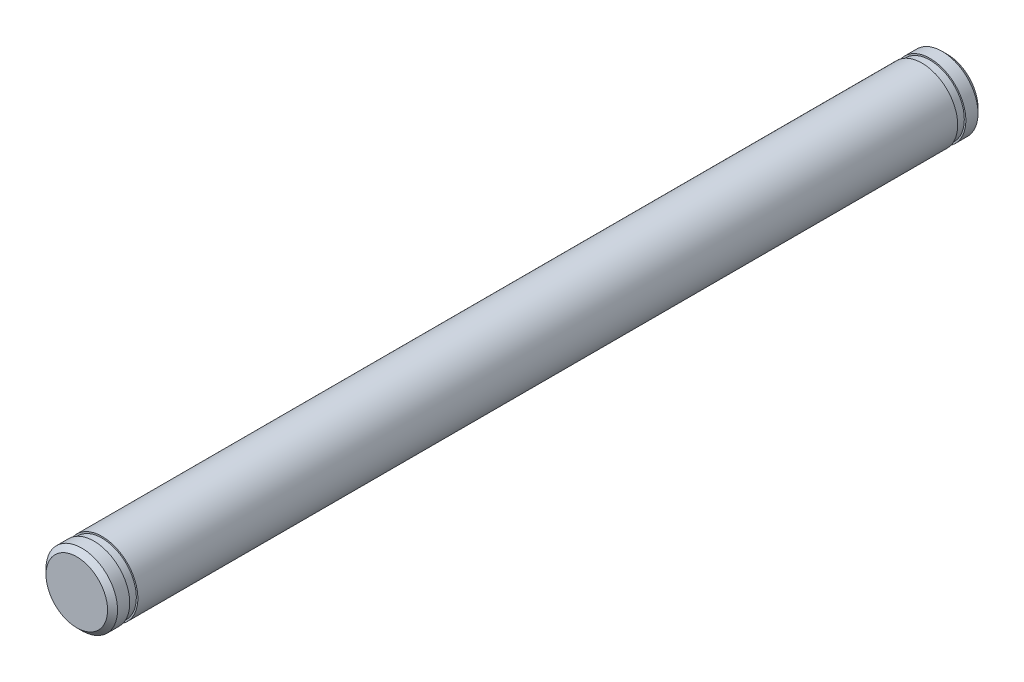
SolidWorks part; units mm, degrees
ref_plane "Front Plane" through (0, 0, 0) normal (0, 0, 1) x (1, 0, 0)
ref_plane "Top Plane" through (0, 0, 0) normal (0, 1, 0) x (1, 0, 0)
ref_plane "Right Plane" through (0, 0, 0) normal (1, 0, 0) x (0, 0, -1)
sketch "Sketch1" plane through (0, 0, 0) normal (0, 0, 1) x (1, 0, 0)
  line L0 (-3.9688, 0) -> (3.9688, 0) construction
  line L5 (0, 3.9688) -> (0, -3.9688) construction
  circle A1 centre (0, 0) radius 3.9688
  point P7 (-3.9688, 0)
  point P8 (3.9688, 0)
  point P12 (0, -3.9688)
  point P13 (0, 3.9688)
  dimension "Diameter" = 7.9375
sketch "Sketch2" plane through (0, 0, 0) normal (1, 0, 0) x (0, 0, -1)
  line L0 (-40.3225, -3.9688) -> (-40.3225, 3.9687) construction
  line L1 (48.26, -3.9688) -> (-48.26, -3.9688)
  line L2 (48.26, -3.9688) -> (48.26, 3.9688)
  line L3 (48.26, 3.9688) -> (-48.26, 3.9688)
  line L4 (-48.26, -3.9688) -> (-48.26, 3.9688)
  line L5 (48.26, -3.9688) -> (-48.26, 3.9688) construction
  line L6 (48.26, 3.9688) -> (-48.26, -3.9688) construction
  line L7 (40.3225, -3.9688) -> (40.3225, 3.9687) construction
  line L8 (-48.26, 3.4131) -> (-47.7044, 3.9687) construction
  point P0 (0, 0)
  point P8 (-48.26, 3.9688)
  point P9 (48.26, 3.9688)
  point P14 (-40.3225, 3.9687)
  point P15 (-40.3225, -3.9688)
  point P16 (40.3225, 3.9687)
  point P17 (40.3225, -3.9688)
  point P25 (0, -3.9688)
  dimension "Length" = 96.52
  dimension "D1" = 7.9375
  dimension "D2" = 7.9375
  dimension "Chamfer Typ," = 45
  dimension "D4" = 0.5556
sketch "Sketch3" plane through (0, 0, 0) normal (0, 0, 1) x (1, 0, 0)
  circle A0 centre (0, 0) radius 3.9688 construction
  circle A1 centre (0, 0) radius 3.9688
extrude "Boss-Extrude1" add sketch "Sketch3" along normal up to vertex (48.26 mm away) and the other way up to vertex (48.26 mm away) up to point (0, 3.9688, 48.26) other way up to point (0, 3.9688, -48.26)
chamfer "Chamfer1" distance 0.5556 angle 45 2 edges at (3.9688, 0, -48.26) (3.9688, 0, 48.26)
sketch "Sketch4" plane through (0, 0, 48.26) normal (0, 0, 1) x (1, 0, 0)
  circle A0 centre (0, 0) radius 18.1151
  circle A1 centre (0, 0) radius 3.8
  dimension "D1" = 7.6
extrude "Cut-Extrude1" cut sketch "Sketch4" against normal blind 0.9 from offset 1.905 offset against normal yes
mirror "Mirror1" about plane through (0, 0, 0) normal (0, 0, 1) of "Cut-Extrude1"
equation "\"D1@Sketch2\"=\"Diameter@Sketch1\""
equation "\"D2@Sketch2\"=\"Diameter@Sketch1\""
equation "\"D1@Chamfer1\"=\"Diameter@Sketch1\"*.07"
equation "\"D4@Sketch2\"=\"Diameter@Sketch1\"*.07"
equation "\"D2@Chamfer1\"=\"Chamfer Typ,@Sketch2\""
